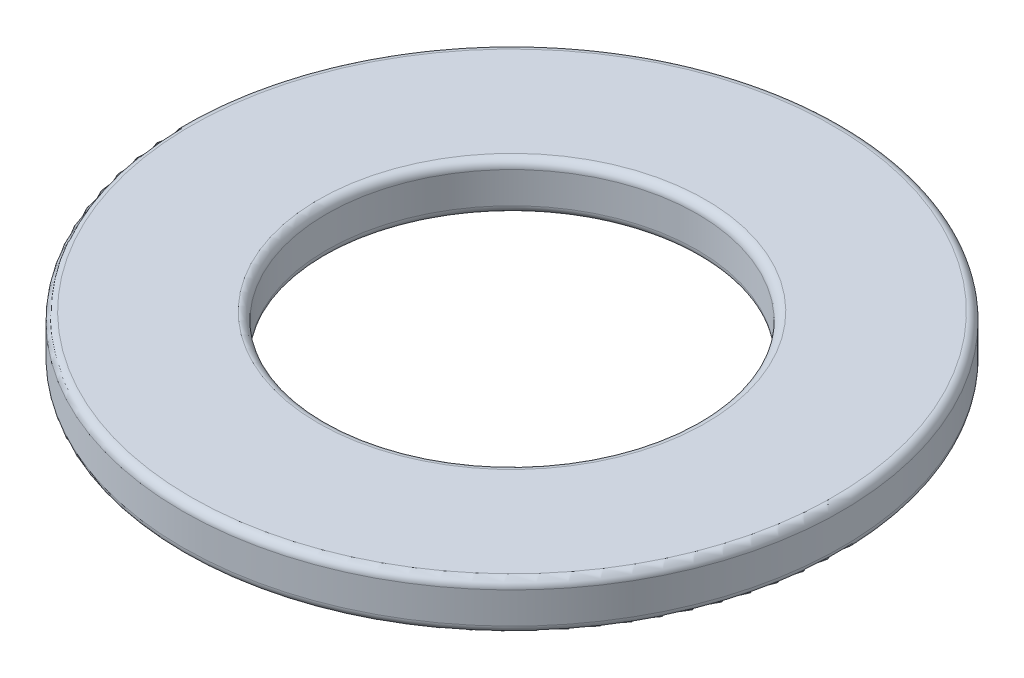
SolidWorks part; units mm, degrees
material "Polyurethane Foam Flexible"
ref_plane "Front Plane" through (0, 0, 0) normal (0, 0, 1) x (1, 0, 0)
ref_plane "Top Plane" through (0, 0, 0) normal (0, 1, 0) x (1, 0, 0)
ref_plane "Right Plane" through (0, 0, 0) normal (1, 0, 0) x (0, 0, -1)
sketch "Sketch2" plane through (0, 0, 0) normal (0, 1, 0) x (1, 0, 0)
  circle A0 centre (0, 0) radius 112.5
  circle A1 centre (0, 0) radius 200
  dimension "D1" = 225
  dimension "D2" = 400
extrude "Boss-Extrude1" add sketch "Sketch2" along normal blind 29
fillet "Fillet1" radius 5 4 edges at (0, 29, 112.5) (0, 0, 112.5) (0, 0, 200) (0, 29, 200)
